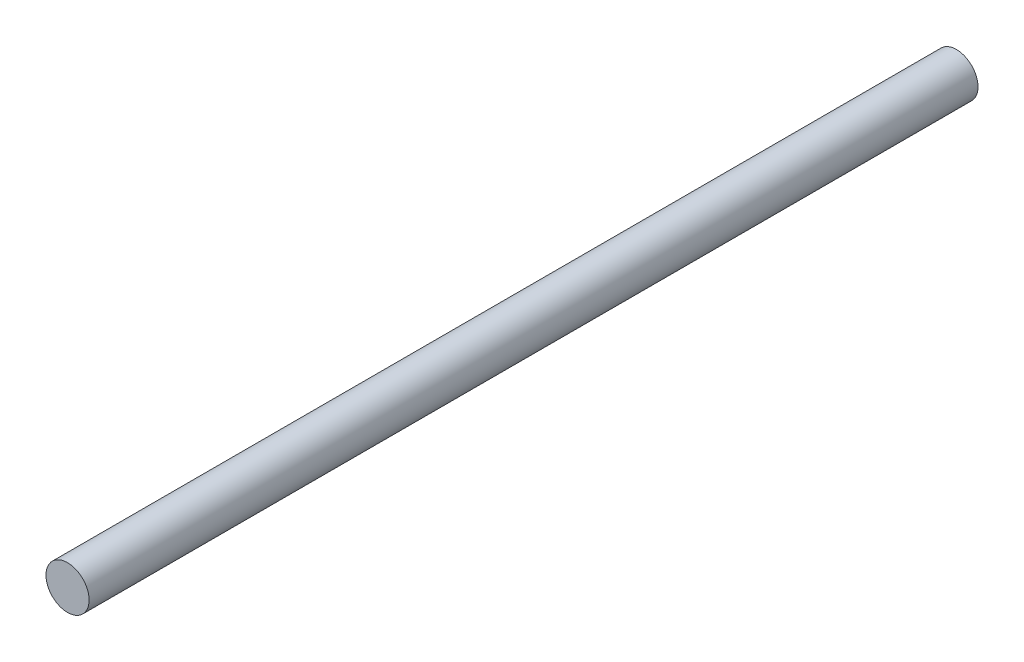
SolidWorks part; units mm, degrees
material "ABS"
ref_plane "Front Plane" through (0, 0, 0) normal (0, 0, 1) x (1, 0, 0)
ref_plane "Top Plane" through (0, 0, 0) normal (0, 1, 0) x (1, 0, 0)
ref_plane "Right Plane" through (0, 0, 0) normal (1, 0, 0) x (0, 0, -1)
sketch "Sketch1" plane through (0, 0, 0) normal (0, 0, 1) x (1, 0, 0)
  circle A0 centre (0, 0) radius 2.5
  dimension "D1" = 5
extrude "Boss-Extrude1" add sketch "Sketch1" along normal blind 103
